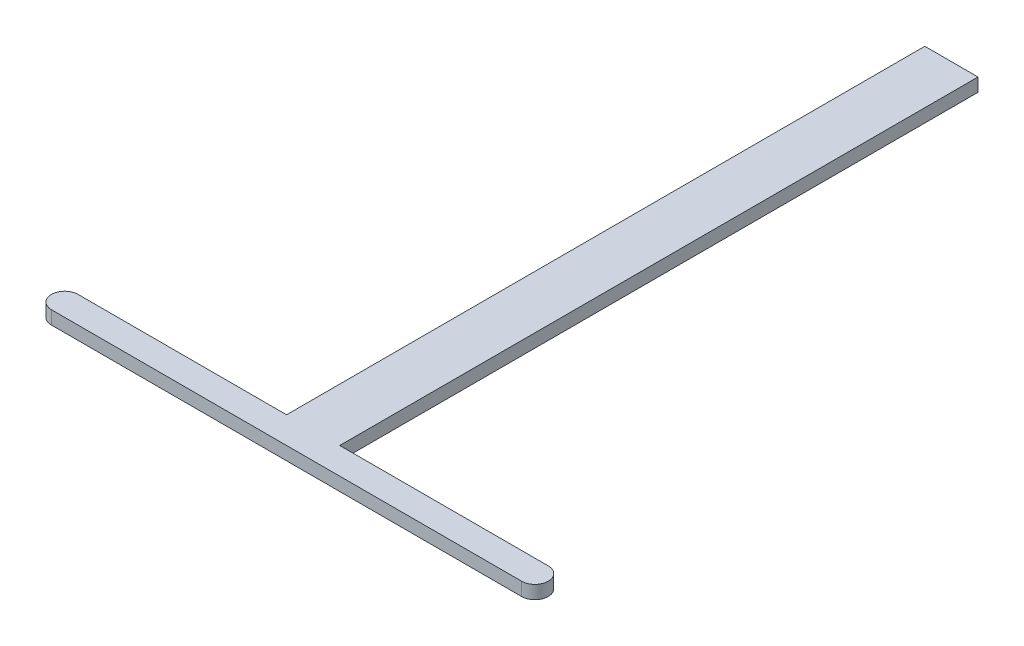
SolidWorks part; units mm, degrees
ref_plane "Front Plane" through (0, 0, 0) normal (0, 0, 1) x (1, 0, 0)
ref_plane "Top Plane" through (0, 0, 0) normal (0, 1, 0) x (1, 0, 0)
ref_plane "Right Plane" through (0, 0, 0) normal (1, 0, 0) x (0, 0, -1)
sketch "Sketch1" plane through (0, 0, 0) normal (0, 1, 0) x (1, 0, 0)
  line L0 (-6.35, 0) -> (-56.134, 0)
  line L1 (-6.35, 152.4) -> (6.35, 152.4)
  line L2 (-6.35, 152.4) -> (-6.35, 0)
  line L4 (6.35, 152.4) -> (6.35, 0)
  line L5 (56.134, 0) -> (6.35, 0)
  line L7 (56.134, -6.35) -> (-56.134, -6.35)
  arc A0 (-56.134, 0) -> (-56.134, -6.35) centre (-56.134, -3.175) ccw
  arc A1 (56.134, -6.35) -> (56.134, 0) centre (56.134, -3.175) ccw
  dimension "D4" = 6.35
  dimension "D5" = 6.35
  dimension "D2" = 12.7
  dimension "D3" = 6.35
extrude "Boss-Extrude1" add sketch "Sketch1" along normal blind 3.175
sketch "Sketch2" plane through (0, 3.175, 0) normal (0, 1, 0) x (1, 0, 0)
  line L0 (-6.35, 150.4) -> (-4.8695, 149.4)
  line L1 (-6.35, 152.4) -> (-6.35, 0) construction
  line L2 (-4.8695, 149.4) -> (-4.8695, 147.4)
  line L3 (-4.8695, 147.4) -> (-6.35, 146.4)
  line L4 (-6.35, 146.4) -> (-6.35, 150.4)
  line L5 (-6.35, 150.4) -> (6.35, 150.4) construction
  line L6 (6.35, 0) -> (6.35, 152.4) construction
  line L7 (-6.35, 146.4) -> (6.35, 146.4) construction
  line L8 (-4.8695, 149.4) -> (6.35, 149.4) construction
  line L9 (-4.8695, 147.4) -> (6.35, 147.4) construction
  line L10 (6.35, 152.4) -> (-6.35, 152.4) construction
  dimension "D1" = 2
  dimension "D2" = 1
  dimension "D3" = 1
  dimension "D4" = 2
